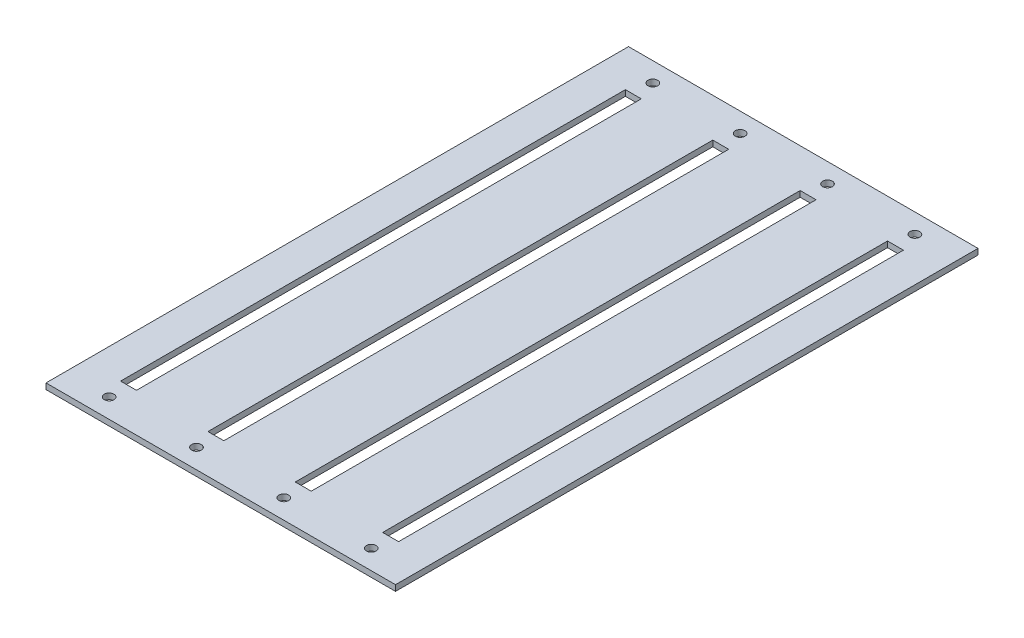
SolidWorks part; units mm, degrees
ref_plane "Front Plane" through (0, 0, 0) normal (0, 0, 1) x (1, 0, 0)
ref_plane "Top Plane" through (0, 0, 0) normal (0, 1, 0) x (1, 0, 0)
ref_plane "Right Plane" through (0, 0, 0) normal (1, 0, 0) x (0, 0, -1)
sketch "Sketch2" plane through (0, 0, 0) normal (0, 1, 0) x (1, 0, 0)
  line L1 (-90, -150) -> (90, -150)
  line L2 (-90, -150) -> (-90, 150)
  line L3 (-90, 150) -> (90, 150)
  line L4 (90, -150) -> (90, 150)
  line L5 (-90, -150) -> (90, 150) construction
  line L6 (-90, 150) -> (90, -150) construction
  point P0 (0, 0)
  dimension "D1" = 180
  dimension "D2" = 300
extrude "Boss-Extrude1" add sketch "Sketch2" along normal blind 3
sketch "Sketch3" plane through (0, 3, 0) normal (0, 1, 0) x (1, 0, 0)
  line L0 (0, -1000) -> (0, 49000) construction
  line L1 (-90, 150) -> (-90, -150) construction
  line L2 (-71.6, 130) -> (-63.4, 130)
  line L3 (-71.6, 130) -> (-71.6, -130)
  line L4 (-71.6, -130) -> (-63.4, -130)
  line L5 (-63.4, 130) -> (-63.4, -130)
  line L6 (-71.6, 130) -> (-63.4, -130) construction
  line L7 (-71.6, -130) -> (-63.4, 130) construction
  line L8 (-26.6, 130) -> (-18.4, 130)
  line L9 (-26.6, 130) -> (-26.6, -130)
  line L10 (-26.6, -130) -> (-18.4, -130)
  line L11 (-18.4, 130) -> (-18.4, -130)
  line L12 (-71.6, 130) -> (-26.6, 130) construction
  line L13 (71.6, 130) -> (26.6, 130) construction
  line L14 (71.6, -130) -> (63.4, 130) construction
  line L15 (71.6, 130) -> (63.4, -130) construction
  line L16 (18.4, 130) -> (18.4, -130)
  line L17 (26.6, -130) -> (18.4, -130)
  line L18 (26.6, 130) -> (26.6, -130)
  line L19 (26.6, 130) -> (18.4, 130)
  line L20 (63.4, 130) -> (63.4, -130)
  line L21 (71.6, -130) -> (63.4, -130)
  line L22 (71.6, 130) -> (71.6, -130)
  line L23 (71.6, 130) -> (63.4, 130)
  point P1 (-67.5, 0)
  point P24 (67.5, 0)
  dimension "D1" = 18.4
  dimension "D2" = 260
  dimension "D3" = 8.2
  dimension "D5" = 36.8
  dimension "D4" = 2
extrude "Cut-Extrude1" cut sketch "Sketch3" against normal through all
sketch "Sketch4" plane through (0, 3, 0) normal (0, 1, 0) x (1, 0, 0)
  line L0 (-1000, 0) -> (49000, 0) construction
  line L1 (0, -1000) -> (0, 49000) construction
  line L2 (71.6, -130) -> (71.6, -150) construction
  line L3 (-90, -150) -> (90, -150) construction
  line L4 (-928.4, -140) -> (49071.6, -140) construction
  line L5 (63.4, -130) -> (71.6, -130) construction
  line L6 (-26.6, -130) -> (-63.4, -130) construction
  line L7 (-26.6, 130) -> (-26.6, -130) construction
  line L8 (-63.4, -130) -> (-63.4, 130) construction
  line L9 (-26.6, -130) -> (-18.4, -130) construction
  line L10 (-45, -1130) -> (-45, 48870) construction
  circle A0 centre (67.5, -140) radius 2.5
  circle A1 centre (-67.5, -140) radius 2.5
  circle A2 centre (67.5, 140) radius 2.5
  circle A3 centre (-67.5, 140) radius 2.5
  circle A4 centre (-22.5, -140) radius 2.5
  circle A5 centre (22.5, -140) radius 2.5
  circle A6 centre (22.5, 140) radius 2.5
  circle A7 centre (-22.5, 140) radius 2.5
  point P13 (71.6, -140)
  point P17 (67.5, -130)
  point P37 (-45, -130)
  dimension "D1" = 5
extrude "Cut-Extrude2" cut sketch "Sketch4" against normal through all
